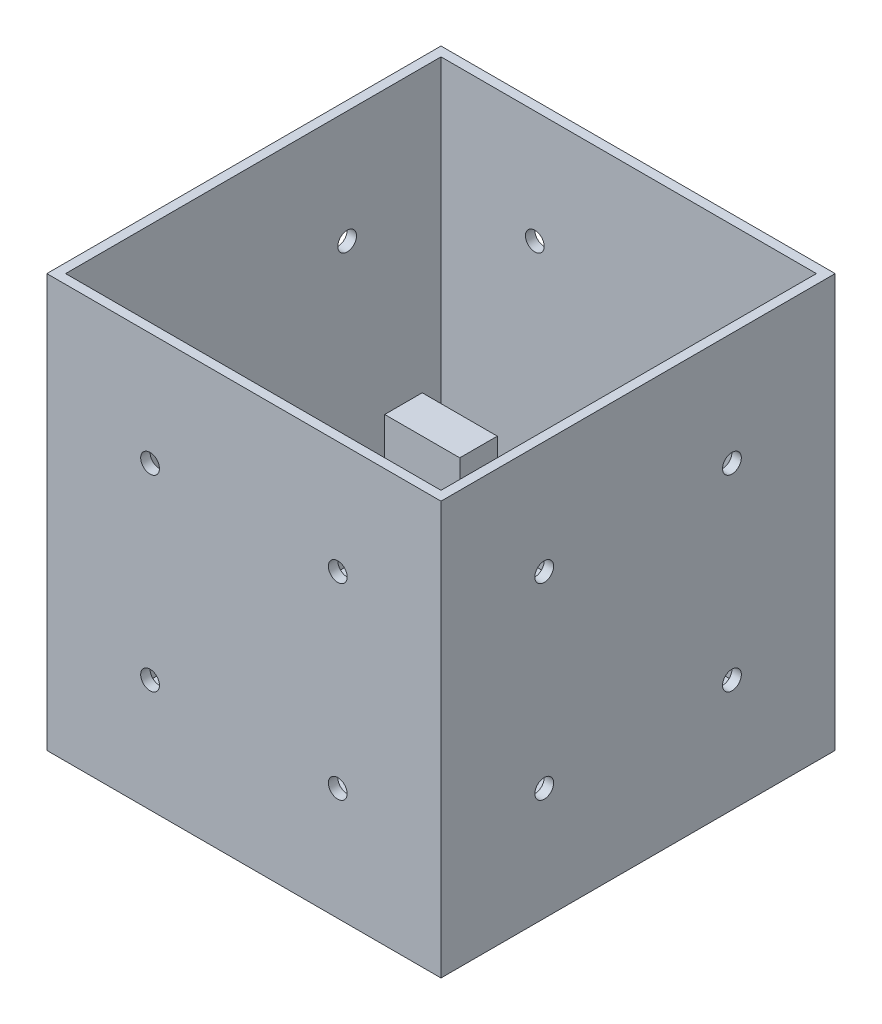
SolidWorks part; units mm, degrees
material "1.4306 (X2CrNi19-11)"
ref_plane "Front Plane" through (0, 0, 0) normal (0, 0, 1) x (1, 0, 0)
ref_plane "Top Plane" through (0, 0, 0) normal (0, 1, 0) x (1, 0, 0)
ref_plane "Right Plane" through (0, 0, 0) normal (1, 0, 0) x (0, 0, -1)
sketch "Sketch2" plane through (0, 0, 0) normal (0, 1, 0) x (1, 0, 0)
  line L1 (-52.5, 52.5) -> (52.5, 52.5)
  line L2 (-52.5, 52.5) -> (-52.5, -52.5)
  line L3 (-52.5, -52.5) -> (52.5, -52.5)
  line L4 (52.5, 52.5) -> (52.5, -52.5)
  line L5 (-52.5, 52.5) -> (52.5, -52.5) construction
  line L6 (-52.5, -52.5) -> (52.5, 52.5) construction
  point P0 (0, 0)
extrude "Boss-Extrude2" add sketch "Sketch2" along normal blind 110
sketch "Sketch3" plane through (0, 110, 0) normal (0, 1, 0) x (1, 0, 0)
  line L1 (-50, 50) -> (50, 50)
  line L2 (-50, 50) -> (-50, -50)
  line L3 (-50, -50) -> (50, -50)
  line L4 (50, 50) -> (50, -50)
  line L5 (-50, 50) -> (50, -50) construction
  line L6 (-50, -50) -> (50, 50) construction
  point P0 (0, 0)
extrude "Cut-Extrude1" cut sketch "Sketch3" against normal blind 105
sketch "Sketch4" plane through (0, 5, 0) normal (0, 1, 0) x (1, 0, 0)
  circle A0 centre (-25, 25) radius 2.5
extrude "Cut-Extrude2" cut sketch "Sketch4" against normal blind 5
sketch "Sketch5" plane through (0, 0, 0) normal (0, -1, 0) x (1, 0, 0)
  circle A0 centre (25, -25) radius 2.5
extrude "Cut-Extrude3" cut sketch "Sketch5" against normal blind 5
sketch "Sketch6" plane through (0, 0, 0) normal (0, -1, 0) x (1, 0, 0)
  circle A0 centre (25, 25) radius 2.5
extrude "Cut-Extrude4" cut sketch "Sketch6" against normal blind 5
sketch "Sketch7" plane through (0, 0, 0) normal (0, -1, 0) x (1, 0, 0)
  circle A0 centre (-25, 25) radius 2.5
extrude "Cut-Extrude5" cut sketch "Sketch7" against normal blind 5
sketch "Sketch8" plane through (-52.5, 0, 0) normal (-1, 0, 0) x (0, 0, 1)
  circle A0 centre (-25, 80) radius 2.5
extrude "Cut-Extrude12" cut sketch "Sketch8" against normal blind 5
sketch "Sketch13" plane through (-52.5, 0, 0) normal (-1, 0, 0) x (0, 0, 1)
  circle A0 centre (-25, 30) radius 2.5
extrude "Cut-Extrude13" cut sketch "Sketch13" against normal blind 5
sketch "Sketch14" plane through (-52.5, 0, 0) normal (-1, 0, 0) x (0, 0, 1)
  circle A0 centre (25, 80) radius 2.5
extrude "Cut-Extrude14" cut sketch "Sketch14" against normal blind 5
sketch "Sketch15" plane through (-52.5, 0, 0) normal (-1, 0, 0) x (0, 0, 1)
  circle A0 centre (25, 30) radius 2.5
extrude "Cut-Extrude15" cut sketch "Sketch15" against normal blind 5
sketch "Sketch16" plane through (0, 0, -52.5) normal (0, 0, -1) x (-1, 0, 0)
  circle A0 centre (25, 80) radius 2.5
extrude "Cut-Extrude16" cut sketch "Sketch16" against normal blind 5
sketch "Sketch17" plane through (0, 0, -52.5) normal (0, 0, -1) x (-1, 0, 0)
  circle A0 centre (25, 30) radius 2.5
extrude "Cut-Extrude17" cut sketch "Sketch17" against normal blind 5
sketch "Sketch18" plane through (0, 0, -52.5) normal (0, 0, -1) x (-1, 0, 0)
  circle A0 centre (-25, 80) radius 2.5
extrude "Cut-Extrude18" cut sketch "Sketch18" against normal blind 5
sketch "Sketch19" plane through (0, 0, -52.5) normal (0, 0, -1) x (-1, 0, 0)
  circle A0 centre (-25, 30) radius 2.5
extrude "Cut-Extrude19" cut sketch "Sketch19" against normal blind 5
sketch "Sketch20" plane through (52.5, 0, 0) normal (1, 0, 0) x (0, 0, -1)
  circle A0 centre (25, 80) radius 2.5
extrude "Cut-Extrude20" cut sketch "Sketch20" against normal blind 5
sketch "Sketch21" plane through (52.5, 0, 0) normal (1, 0, 0) x (0, 0, -1)
  circle A0 centre (-25, 80) radius 2.5
extrude "Cut-Extrude21" cut sketch "Sketch21" against normal blind 5
sketch "Sketch22" plane through (52.5, 0, 0) normal (1, 0, 0) x (0, 0, -1)
  circle A0 centre (25, 30) radius 2.5
extrude "Cut-Extrude22" cut sketch "Sketch22" against normal blind 5
sketch "Sketch23" plane through (52.5, 0, 0) normal (1, 0, 0) x (0, 0, -1)
  circle A0 centre (-25, 30) radius 2.5
extrude "Cut-Extrude23" cut sketch "Sketch23" against normal blind 5
sketch "Sketch24" plane through (0, 0, 52.5) normal (0, 0, 1) x (1, 0, 0)
  circle A0 centre (-25, 80) radius 2.5
extrude "Cut-Extrude24" cut sketch "Sketch24" against normal blind 5
sketch "Sketch25" plane through (0, 0, 52.5) normal (0, 0, 1) x (1, 0, 0)
  circle A0 centre (25, 80) radius 2.5
extrude "Cut-Extrude25" cut sketch "Sketch25" against normal blind 5
sketch "Sketch26" plane through (0, 0, 52.5) normal (0, 0, 1) x (1, 0, 0)
  circle A0 centre (-25, 30) radius 2.5
extrude "Cut-Extrude26" cut sketch "Sketch26" against normal blind 5
sketch "Sketch27" plane through (0, 0, 52.5) normal (0, 0, 1) x (1, 0, 0)
  circle A0 centre (25, 30) radius 2.5
extrude "Cut-Extrude27" cut sketch "Sketch27" against normal blind 5
sketch "Sketch28" plane through (0, 5, 0) normal (0, 1, 0) x (1, 0, 0)
  line L1 (-10, 5) -> (10, 5)
  line L2 (-10, 5) -> (-10, -5)
  line L3 (-10, -5) -> (10, -5)
  line L4 (10, 5) -> (10, -5)
  line L5 (-10, 5) -> (10, -5) construction
  line L6 (-10, -5) -> (10, 5) construction
  point P0 (0, 0)
extrude "Boss-Extrude3" add sketch "Sketch28" along normal blind 70
